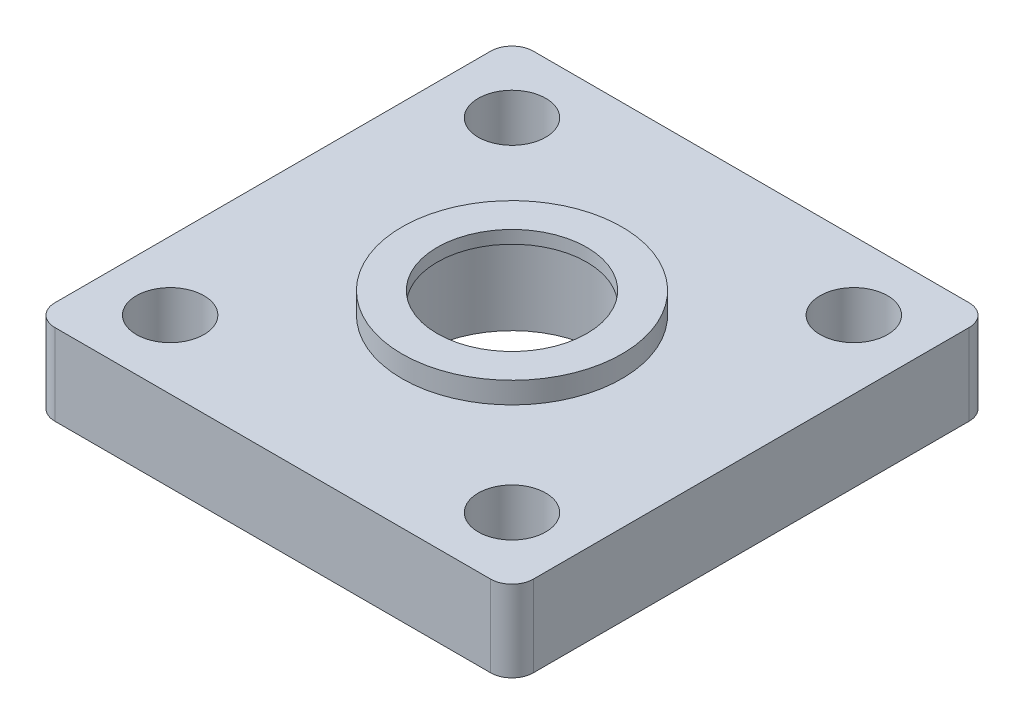
SolidWorks part; units mm, degrees
material "1.4000 (X6Cr13)"
ref_plane "前视基准面" through (0, 0, 0) normal (0, 0, 1) x (1, 0, 0)
ref_plane "上视基准面" through (0, 0, 0) normal (0, 1, 0) x (1, 0, 0)
ref_plane "右视基准面" through (0, 0, 0) normal (1, 0, 0) x (0, 0, -1)
sketch "草图1" plane through (0, 0, 0) normal (0, 1, 0) x (1, 0, 0)
  line L1 (-56, 56) -> (56, 56)
  line L2 (-56, 56) -> (-56, -56)
  line L3 (-56, -56) -> (56, -56)
  line L4 (56, 56) -> (56, -56)
  line L5 (-56, 56) -> (56, -56) construction
  line L6 (-56, -56) -> (56, 56) construction
  point P0 (0, 0)
  dimension "D1" = 112
  dimension "D2" = 112
extrude "凸台-拉伸1" add sketch "草图1" along normal blind 19
sketch "草图2" plane through (0, 19, 0) normal (0, 1, 0) x (1, 0, 0)
  circle A0 centre (0, 0) radius 25.75
  dimension "D1" = 51.5
extrude "凸台-拉伸2" add sketch "草图2" along normal blind 5
sketch "草图3" plane through (0, 0, 0) normal (0, -1, 0) x (1, 0, 0)
  line L1 (-50, 50) -> (50, 50)
  line L2 (-50, 50) -> (-50, -50)
  line L3 (-50, -50) -> (50, -50)
  line L4 (50, 50) -> (50, -50)
  line L5 (-50, 50) -> (50, -50) construction
  line L6 (-50, -50) -> (50, 50) construction
  point P0 (0, 0)
  dimension "D1" = 100
  dimension "D2" = 100
extrude "凸台-拉伸3" add sketch "草图3" along normal blind 5
sketch "草图4" plane through (0, -5, 0) normal (0, -1, 0) x (1, 0, 0)
  circle A0 centre (0, 0) radius 30
  dimension "D1" = 60
extrude "切除-拉伸1" cut sketch "草图4" against normal blind 5
sketch "草图5" plane through (0, 0, 0) normal (0, -1, 0) x (1, 0, 0)
  circle A0 centre (0, 0) radius 26
  dimension "D1" = 52
extrude "切除-拉伸2" cut sketch "草图5" against normal blind 1
sketch "草图6" plane through (0, 1, 0) normal (0, -1, 0) x (1, 0, 0)
  circle A0 centre (0, 0) radius 21
  dimension "D1" = 42
extrude "切除-拉伸3" cut sketch "草图6" against normal blind 20
sketch "草图7" plane through (0, 24, 0) normal (0, 1, 0) x (1, 0, 0)
  circle A0 centre (0, 0) radius 17.5
  dimension "D1" = 35
extrude "切除-拉伸4" cut sketch "草图7" against normal through all
sketch "草图8" plane through (0, 19, 0) normal (0, 1, 0) x (1, 0, 0)
  line L1 (-40, 40) -> (40, 40) construction
  line L2 (-40, 40) -> (-40, -40) construction
  line L3 (-40, -40) -> (40, -40) construction
  line L4 (40, 40) -> (40, -40) construction
  line L5 (-40, 40) -> (40, -40) construction
  line L6 (-40, -40) -> (40, 40) construction
  circle A0 centre (-40, 40) radius 7.9
  circle A1 centre (40, 40) radius 7.9
  circle A2 centre (40, -40) radius 7.9
  circle A3 centre (-40, -40) radius 7.9
  point P0 (0, 0)
  dimension "D3" = 15.8
  dimension "D4" = 15.8
  dimension "D5" = 15.8
  dimension "D6" = 15.8
  dimension "D1" = 80
  dimension "D2" = 80
extrude "切除-拉伸5" cut sketch "草图8" against normal through all
fillet "圆角1" radius 5 8 edges at (50, -2.5, 50) (-50, -2.5, 50) (-50, -2.5, -50) (50, -2.5, -50) (56, 9.5, -56) (56, 9.5, 56) (-56, 9.5, 56) (-56, 9.5, -56)
fillet "圆角2" radius 1 1 edges at (0, 21, -21)
